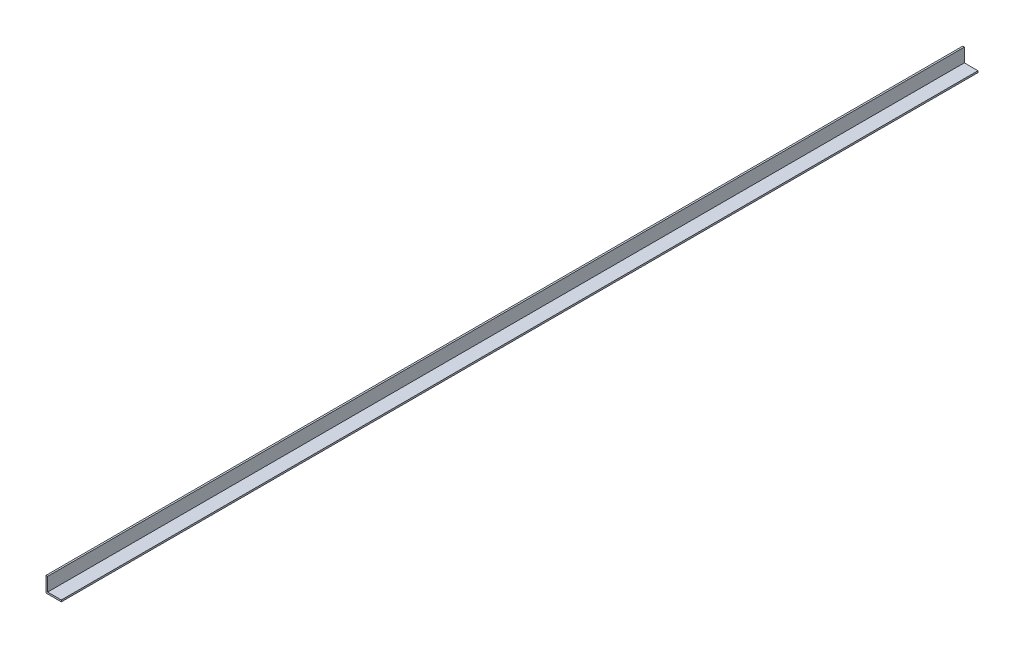
SolidWorks part; units mm, degrees
material "ASTM A36 Acero"
ref_plane "Alzado" through (0, 0, 0) normal (0, 0, 1) x (1, 0, 0)
ref_plane "Planta" through (0, 0, 0) normal (0, 1, 0) x (1, 0, 0)
ref_plane "Vista lateral" through (0, 0, 0) normal (1, 0, 0) x (0, 0, -1)
sketch "Croquis1" plane through (0, 0, 0) normal (0, 0, 1) x (1, 0, 0)
  line L0 (0, 102) -> (0, 0)
  line L1 (0, 0) -> (102, 0)
  line L2 (102, 0) -> (102, 11.1)
  line L3 (102, 11.1) -> (11.1, 11.1)
  line L4 (11.1, 11.1) -> (11.1, 102)
  line L5 (11.1, 102) -> (0, 102)
  dimension "D1" = 11.1
  dimension "D2" = 102
extrude "Saliente-Extruir1" add sketch "Croquis1" against normal blind 6100
